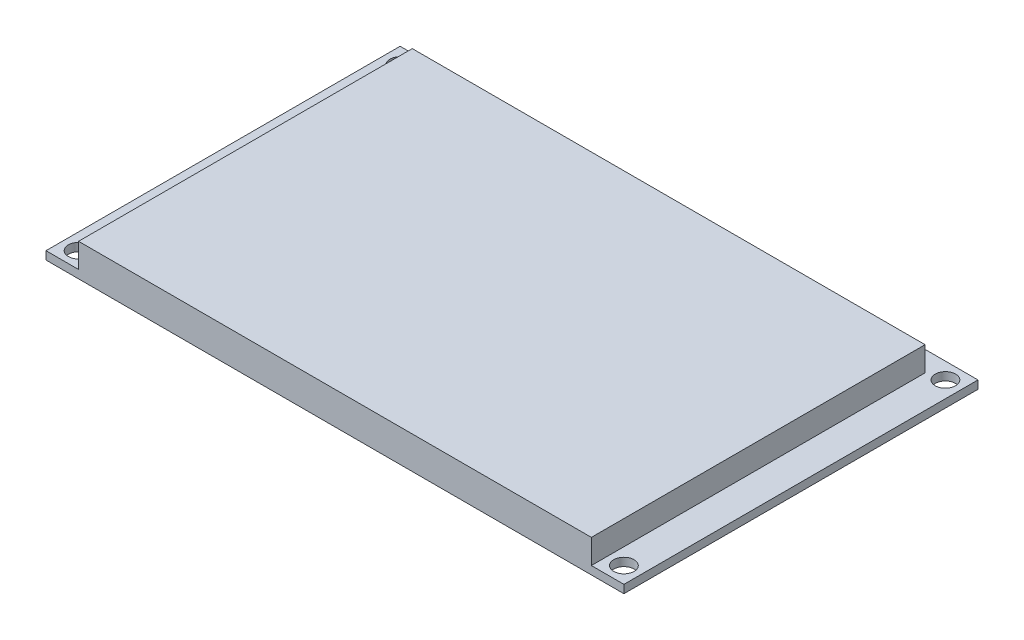
SolidWorks part; units mm, degrees
ref_plane "前视基准面" through (0, 0, 0) normal (0, 0, 1) x (1, 0, 0)
ref_plane "上视基准面" through (0, 0, 0) normal (0, 1, 0) x (1, 0, 0)
ref_plane "右视基准面" through (0, 0, 0) normal (1, 0, 0) x (0, 0, -1)
sketch "草图1" plane through (0, 0, 0) normal (0, 1, 0) x (1, 0, 0)
  line L1 (-35.5, 21.75) -> (35.5, 21.75)
  line L2 (-35.5, 21.75) -> (-35.5, -21.75)
  line L3 (-35.5, -21.75) -> (35.5, -21.75)
  line L4 (35.5, 21.75) -> (35.5, -21.75)
  line L5 (-35.5, 21.75) -> (35.5, -21.75) construction
  line L6 (-35.5, -21.75) -> (35.5, 21.75) construction
  point P0 (0, 0)
  dimension "D1" = 71
  dimension "D2" = 43.5
extrude "凸台-拉伸1" add sketch "草图1" along normal blind 1
sketch "草图6" plane through (0, 1, 0) normal (0, 1, 0) x (1, 0, 0)
  line L1 (-33.5, 19.75) -> (33.5, 19.75)
  line L2 (-33.5, 19.75) -> (-33.5, -19.75)
  line L3 (-33.5, -19.75) -> (33.5, -19.75)
  line L4 (33.5, 19.75) -> (33.5, -19.75)
  line L5 (-33.5, 19.75) -> (33.5, -19.75) construction
  line L6 (-33.5, -19.75) -> (33.5, 19.75) construction
  circle A0 centre (-33.5, 19.75) radius 1.25
  circle A1 centre (33.5, 19.75) radius 1.25
  circle A2 centre (33.5, -19.75) radius 1.25
  circle A3 centre (-33.5, -19.75) radius 1.25
  point P0 (0, 0)
  dimension "D1" = 67
  dimension "D2" = 39.5
extrude "切除-拉伸1" cut sketch "草图6" against normal up to next contours A0 | A3 | A1 | A2
sketch "草图4" plane through (0, 1, 0) normal (0, 1, 0) x (1, 0, 0)
  line L0 (-35.5, -21.75) -> (35.5, -21.75) construction
  line L1 (-31.5, 19.25) -> (31.5, 19.25)
  line L2 (-31.5, 19.25) -> (-31.5, -21.75)
  line L3 (-31.5, -21.75) -> (31.5, -21.75)
  line L4 (31.5, 19.25) -> (31.5, -21.75)
  line L5 (-31.5, 19.25) -> (31.5, -21.75) construction
  line L6 (-31.5, -21.75) -> (31.5, 19.25) construction
  line L7 (0, 0) -> (0, 25.8344) construction
  line L8 (-35.5, 21.75) -> (-35.5, -21.75) construction
  line L9 (35.5, -21.75) -> (35.5, 21.75) construction
  point P0 (0, -1.25)
  point P9 (0, 0)
  point P14 (0, 0)
  dimension "D1" = 63
  dimension "D2" = 41
extrude "凸台-拉伸2" add sketch "草图4" along normal blind 3
